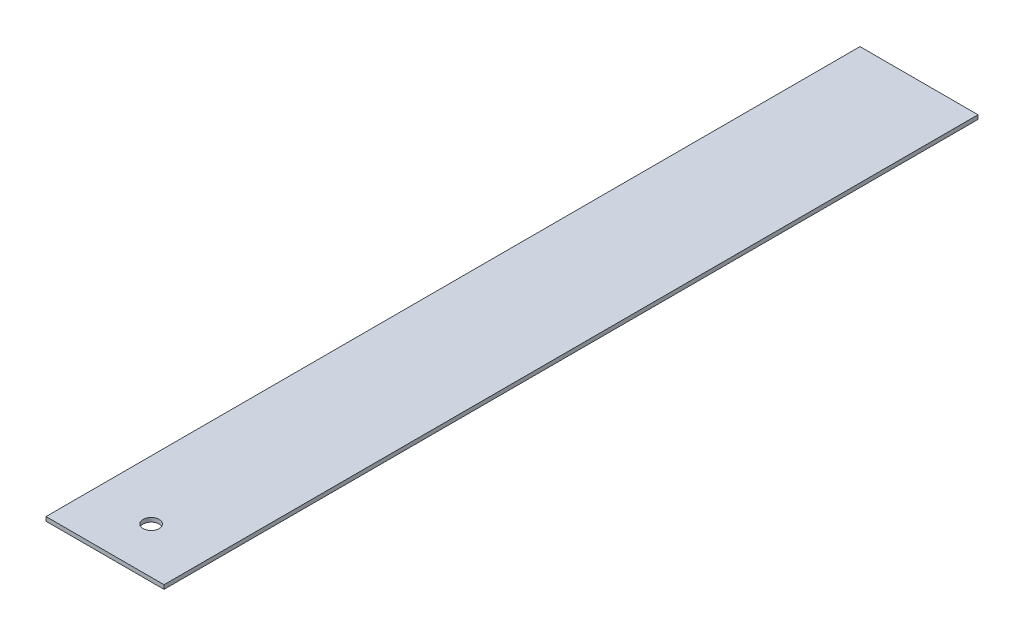
SolidWorks part; units mm, degrees
ref_plane "Front Plane" through (0, 0, 0) normal (0, 0, 1) x (1, 0, 0)
ref_plane "Top Plane" through (0, 0, 0) normal (0, 1, 0) x (1, 0, 0)
ref_plane "Right Plane" through (0, 0, 0) normal (1, 0, 0) x (0, 0, -1)
sketch "Sketch1" plane through (0, 0, 0) normal (0, 1, 0) x (1, 0, 0)
  line L1 (0, 0) -> (22.098, 0)
  line L2 (0, 0) -> (0, 152.4)
  line L3 (0, 152.4) -> (22.098, 152.4)
  line L4 (22.098, 0) -> (22.098, 152.4)
  dimension "D1" = 22.098
  dimension "D2" = 152.4
extrude "Boss-Extrude1" add sketch "Sketch1" along normal blind 0.762
sketch "Sketch2" plane through (0, 0.762, 0) normal (0, 1, 0) x (1, 0, 0)
  line L0 (22.098, 0) -> (22.098, 152.4) construction
  line L1 (0, 0) -> (22.098, 0) construction
  circle A0 centre (11.049, 8.636) radius 1.5
  dimension "D3" = 3
  dimension "D1" = 11.049
  dimension "D2" = 8.636
extrude "Cut-Extrude1" cut sketch "Sketch2" against normal up to next contours A0
